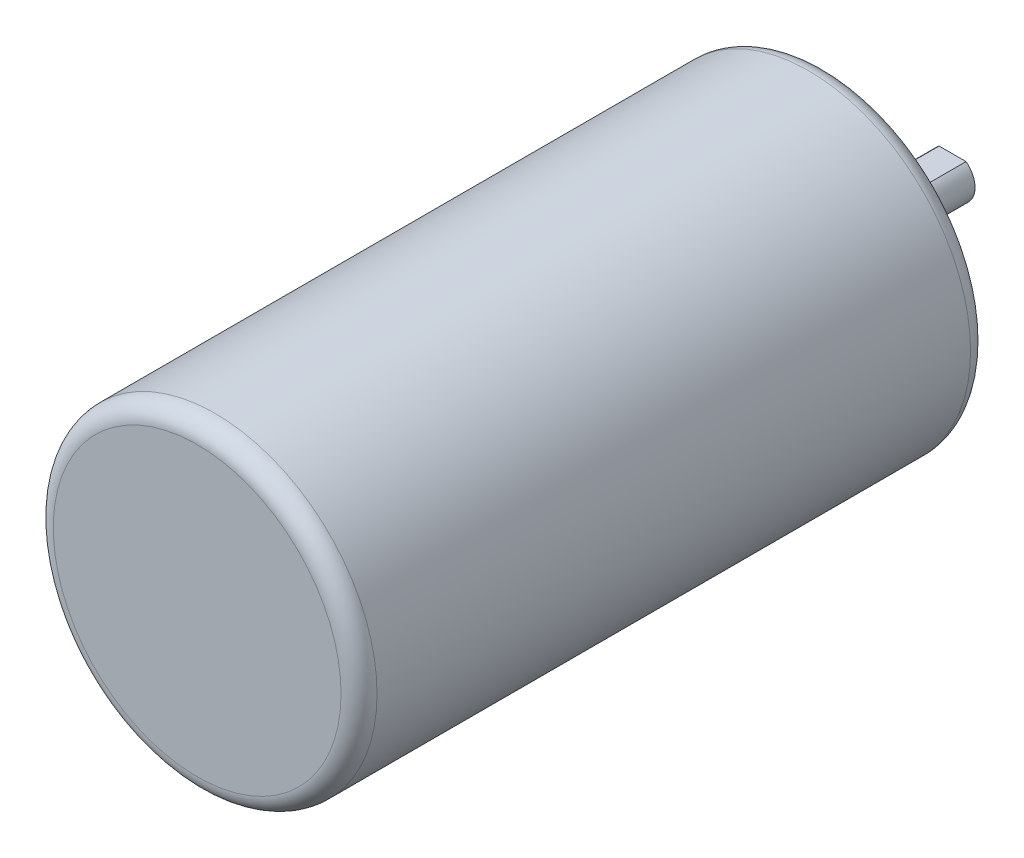
SolidWorks part; units mm, degrees
ref_plane "Front Plane" through (0, 0, 0) normal (0, 0, 1) x (1, 0, 0)
ref_plane "Top Plane" through (0, 0, 0) normal (0, 1, 0) x (1, 0, 0)
ref_plane "Right Plane" through (0, 0, 0) normal (1, 0, 0) x (0, 0, -1)
sketch "Sketch1" plane through (0, 0, 0) normal (0, 0, 1) x (1, 0, 0)
  circle A0 centre (0, 0) radius 18
  dimension "D1" = 36
extrude "Boss-Extrude1" add sketch "Sketch1" along normal blind 70
sketch "Sketch2" plane through (0, 0, 0) normal (0, 0, -1) x (-1, 0, 0)
  line L0 (-1.5, 2) -> (1.5, 2)
  arc A0 (-1.5, 2) -> (1.5, 2) centre (0, 0) ccw
  dimension "D1" = 5
  dimension "D2" = 4.5
extrude "Boss-Extrude2" add sketch "Sketch2" along normal blind 14
fillet "Fillet1" radius 2 2 edges at (18, 0, 70) (18, 0, 0)
